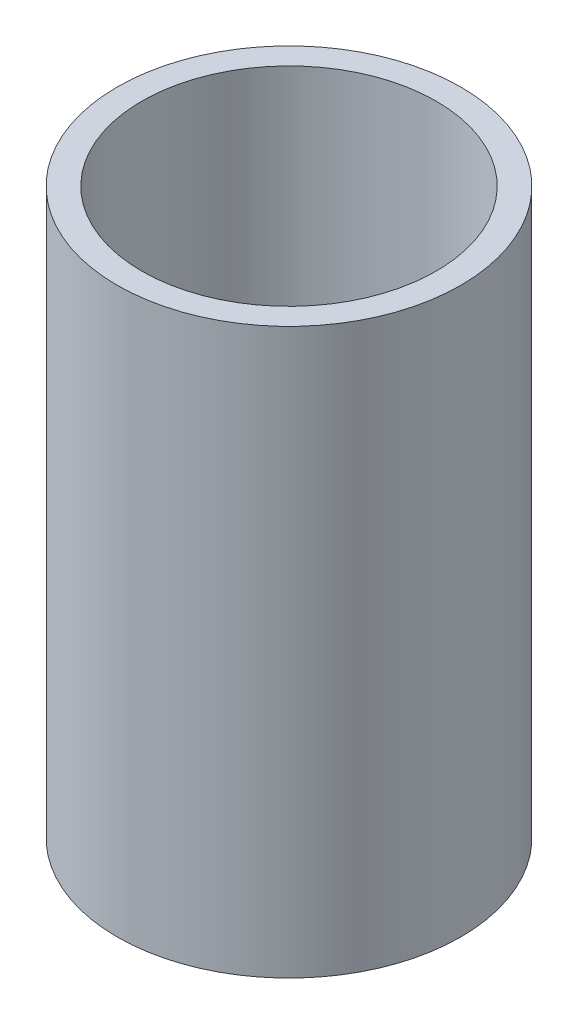
SolidWorks part; units mm, degrees
material "Brass"
ref_plane "Front Plane" through (0, 0, 0) normal (0, 0, 1) x (1, 0, 0)
ref_plane "Top Plane" through (0, 0, 0) normal (0, 1, 0) x (1, 0, 0)
ref_plane "Right Plane" through (0, 0, 0) normal (1, 0, 0) x (0, 0, -1)
sketch "Sketch1" plane through (0, 0, 0) normal (0, 1, 0) x (1, 0, 0)
  circle A0 centre (0, 0) radius 3
  circle A1 centre (0, 0) radius 3.5
  dimension "D1" = 6
  dimension "D2" = 7
extrude "Boss-Extrude1" add sketch "Sketch1" along normal blind 11.5
